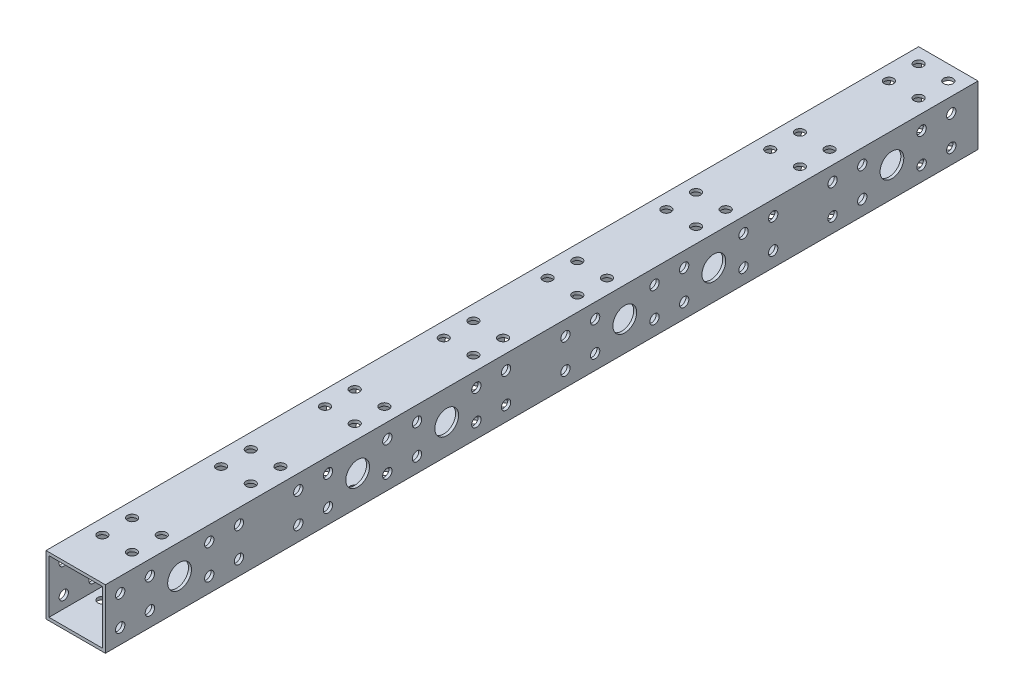
SolidWorks part; units mm, degrees
ref_plane "前视基准面" through (0, 0, 0) normal (0, 0, 1) x (1, 0, 0)
ref_plane "上视基准面" through (0, 0, 0) normal (0, 1, 0) x (1, 0, 0)
ref_plane "右视基准面" through (0, 0, 0) normal (1, 0, 0) x (0, 0, -1)
other "Configuration Table"
sketch "草图1" plane through (0, 0, 0) normal (0, 0, 1) x (1, 0, 0)
  line L1 (0, 0) -> (20, 0)
  line L2 (0, 0) -> (0, -20)
  line L3 (0, -20) -> (20, -20)
  line L4 (20, 0) -> (20, -20)
  dimension "D1" = 20
  dimension "D2" = 20
extrude "拉伸-薄壁1" add sketch "草图1" along normal blind 294 thin
sketch "草图2" plane through (0, 0, 0) normal (-1, 0, 0) x (0, 0, 1)
  line L0 (284, 0) -> (284, -20) construction
  line L1 (294, 0) -> (0, 0) construction
  line L2 (294, -20) -> (0, -20) construction
  line L3 (294, -10) -> (284, -10) construction
  line L4 (294, 0) -> (294, -20) construction
  circle A0 centre (289, -5) radius 1.575
  circle A1 centre (289, -15) radius 1.575
  circle A2 centre (279, -15) radius 1.575
  circle A3 centre (279, -5) radius 1.575
  circle A4 centre (259, -5) radius 1.575
  circle A5 centre (259, -15) radius 1.575
  circle A6 centre (249, -15) radius 1.575
  circle A7 centre (249, -5) radius 1.575
  circle A8 centre (229, -5) radius 1.575
  circle A9 centre (229, -15) radius 1.575
  circle A10 centre (219, -15) radius 1.575
  circle A11 centre (219, -5) radius 1.575
  circle A12 centre (199, -5) radius 1.575
  circle A13 centre (199, -15) radius 1.575
  circle A14 centre (189, -15) radius 1.575
  circle A15 centre (189, -5) radius 1.575
  circle A16 centre (169, -5) radius 1.575
  circle A17 centre (169, -15) radius 1.575
  circle A18 centre (159, -15) radius 1.575
  circle A19 centre (159, -5) radius 1.575
  circle A20 centre (139, -5) radius 1.575
  circle A21 centre (139, -15) radius 1.575
  circle A22 centre (129, -15) radius 1.575
  circle A23 centre (129, -5) radius 1.575
  circle A24 centre (109, -5) radius 1.575
  circle A25 centre (109, -15) radius 1.575
  circle A26 centre (99, -15) radius 1.575
  circle A27 centre (99, -5) radius 1.575
  circle A28 centre (79, -5) radius 1.575
  circle A29 centre (79, -15) radius 1.575
  circle A30 centre (69, -15) radius 1.575
  circle A31 centre (69, -5) radius 1.575
  circle A32 centre (49, -5) radius 1.575
  circle A33 centre (49, -15) radius 1.575
  circle A34 centre (39, -15) radius 1.575
  circle A35 centre (39, -5) radius 1.575
  circle A36 centre (19, -5) radius 1.575
  circle A37 centre (19, -15) radius 1.575
  circle A38 centre (9, -15) radius 1.575
  circle A39 centre (9, -5) radius 1.575
  circle A40 centre (269, -10) radius 4
  circle A42 centre (209, -10) radius 4
  circle A43 centre (179, -10) radius 4
  circle A45 centre (119, -10) radius 4
  circle A46 centre (89, -10) radius 4
  circle A48 centre (29, -10) radius 4
  circle A49 centre (59, -10) radius 4 [skipped]
  circle A50 centre (149, -10) radius 4 [skipped]
  circle A51 centre (239, -10) radius 4 [skipped]
  dimension "D2" = 3.15
  dimension "D6" = 8
  dimension "D1" = 10
  dimension "D3" = 5
  dimension "D4" = 5
  dimension "D5" = 20
  dimension "D7" = 15
  dimension "D8" = 10
  dimension "D9" = 60
  dimension "D10" = 9
extrude "切除-拉伸1" cut sketch "草图2" against normal through all
sketch "草图3" plane through (0, 0, 0) normal (0, 1, 0) x (1, 0, 0)
  line L0 (0, -10) -> (20, -10) construction
  line L1 (0, -294) -> (0, 0) construction
  line L2 (20, -294) -> (20, 0) construction
  line L3 (0, -30) -> (20, -30) construction
  line L4 (20, 0) -> (0, 0) construction
  line L5 (10, 0) -> (10, -10) construction
  line L6 (10, -60) -> (10, -50) construction
  line L7 (0, -50) -> (20, -50) construction
  circle A0 centre (5, -5) radius 1.575
  circle A1 centre (15, -5) radius 1.575
  circle A2 centre (15, -15) radius 1.575
  circle A3 centre (5, -15) radius 1.575
  circle A4 centre (5, -45) radius 1.575
  circle A5 centre (15, -45) radius 1.575
  circle A6 centre (15, -55) radius 1.575
  circle A7 centre (5, -55) radius 1.575
  circle A8 centre (5, -80) radius 1.575
  circle A9 centre (15, -80) radius 1.575
  circle A10 centre (5, -90) radius 1.575
  circle A11 centre (15, -90) radius 1.575
  circle A12 centre (5, -120) radius 1.575
  circle A13 centre (5, -130) radius 1.575
  circle A14 centre (15, -120) radius 1.575
  circle A15 centre (15, -130) radius 1.575
  circle A16 centre (5, -155) radius 1.575
  circle A17 centre (15, -155) radius 1.575
  circle A18 centre (5, -165) radius 1.575
  circle A19 centre (15, -165) radius 1.575
  circle A20 centre (5, -195) radius 1.575
  circle A21 centre (5, -205) radius 1.575
  circle A22 centre (15, -195) radius 1.575
  circle A23 centre (15, -205) radius 1.575
  circle A24 centre (5, -230) radius 1.575
  circle A25 centre (15, -230) radius 1.575
  circle A26 centre (5, -240) radius 1.575
  circle A27 centre (15, -240) radius 1.575
  circle A28 centre (5, -270) radius 1.575
  circle A29 centre (5, -280) radius 1.575
  circle A30 centre (15, -270) radius 1.575
  circle A31 centre (15, -280) radius 1.575
  dimension "D4" = 3.15
  dimension "D1" = 10
  dimension "D2" = 5
  dimension "D3" = 5
  dimension "D5" = 30
  dimension "D6" = 75
extrude "切除-拉伸2" cut sketch "草图3" against normal through all
